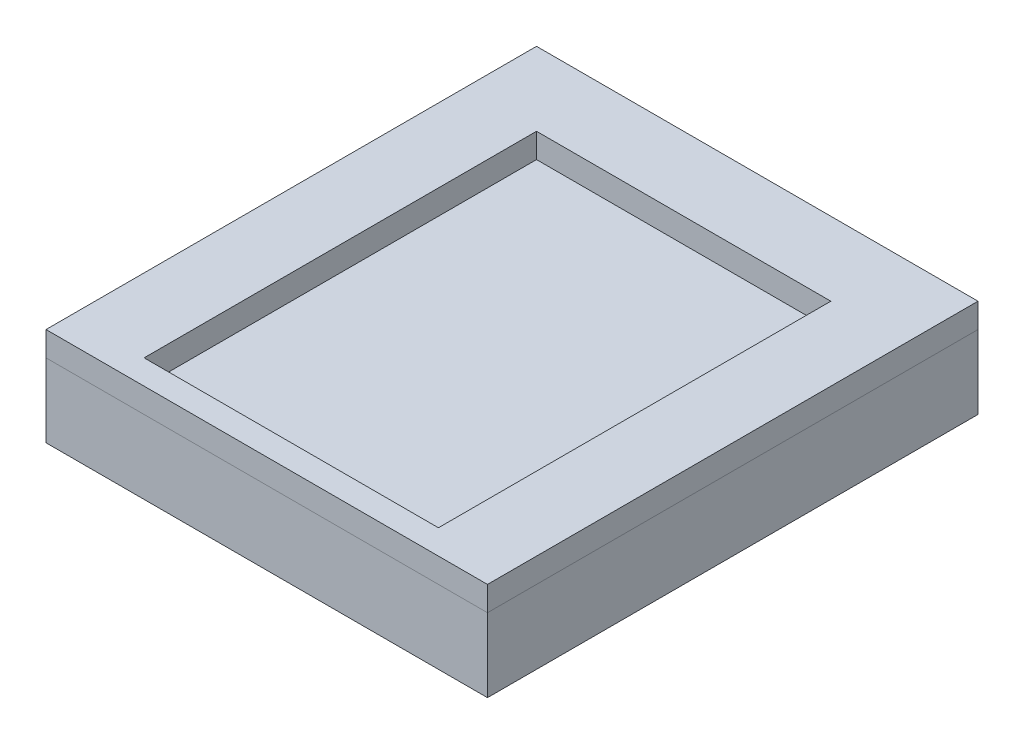
SolidWorks part; units mm, degrees
ref_plane "정면" through (0, 0, 0) normal (0, 0, 1) x (1, 0, 0)
ref_plane "윗면" through (0, 0, 0) normal (0, 1, 0) x (1, 0, 0)
ref_plane "우측면" through (0, 0, 0) normal (1, 0, 0) x (0, 0, -1)
sketch "스케치1" plane through (0, 0, 0) normal (0, 1, 0) x (1, 0, 0)
  line L1 (9, -10) -> (-9, -10)
  line L2 (9, -10) -> (9, 10)
  line L3 (9, 10) -> (-9, 10)
  line L4 (-9, -10) -> (-9, 10)
  line L5 (9, -10) -> (-9, 10) construction
  line L6 (9, 10) -> (-9, -10) construction
  point P0 (0, 0)
  dimension "D1" = 18
  dimension "D2" = 20
extrude "보스-돌출1" add sketch "스케치1" along normal blind 3
sketch "스케치3" plane through (0, 0, 0) normal (0, 1, 0) x (1, 0, 0)
  line L0 (-9, -10) -> (9, -10) construction
  line L1 (-8, 10) -> (8, 10)
  line L2 (-8, 10) -> (-8, -9)
  line L3 (-8, -9) -> (8, -9)
  line L4 (8, 10) -> (8, -9)
  line L5 (-9, 10) -> (-9, -10) construction
  dimension "D1" = 1
  dimension "D2" = 19
  dimension "D3" = 16
  dimension "D4" = 1
extrude "컷-돌출1" cut sketch "스케치3" along normal blind 3 from offset 1
sketch "스케치4" plane through (0, 0, 0) normal (0, 1, 0) x (1, 0, 0)
  line L1 (9, -10) -> (-9, -10)
  line L2 (9, -10) -> (9, 10)
  line L3 (9, 10) -> (-9, 10)
  line L4 (-9, -10) -> (-9, 10)
  line L5 (9, -10) -> (-9, 10) construction
  line L6 (9, 10) -> (-9, -10) construction
  point P0 (0, 0)
extrude "보스-돌출2" add sketch "스케치4" along normal blind 1 from offset 3 separate body
sketch "스케치7" plane through (0, 0, 0) normal (0, 1, 0) x (1, 0, 0)
  line L0 (-9, -10) -> (9, -10) construction
  line L1 (-6, 7) -> (6, 7)
  line L2 (-6, 7) -> (-6, -9)
  line L3 (-6, -9) -> (6, -9)
  line L4 (6, 7) -> (6, -9)
  line L5 (9, -10) -> (9, 10) construction
  dimension "D1" = 12
  dimension "D2" = 16
  dimension "D3" = 1
  dimension "D4" = 3
extrude "컷-돌출3" cut sketch "스케치7" against normal blind 1 from surface at 4 starting at face at (0, 4, 0)
